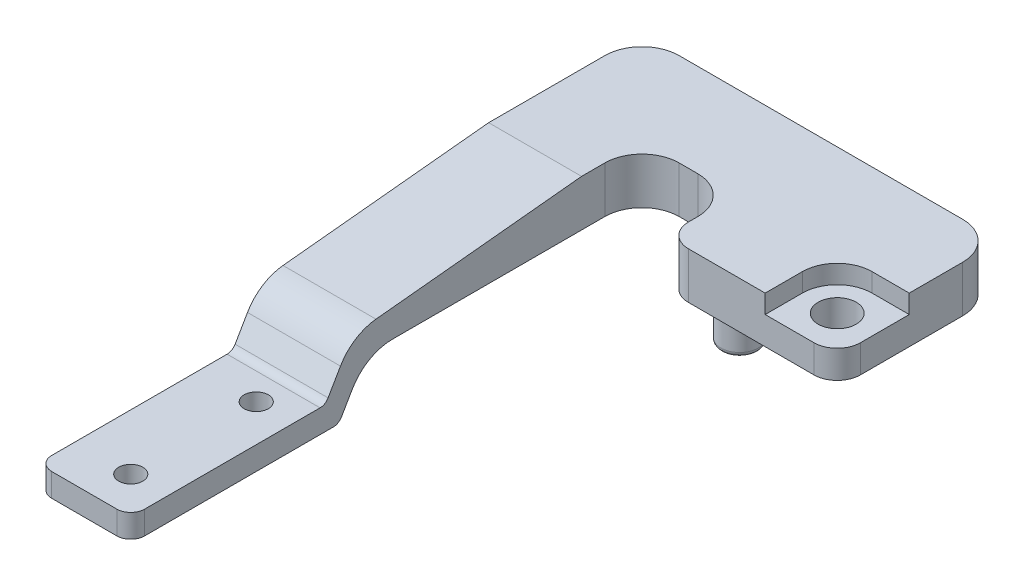
SolidWorks part; units mm, degrees
ref_plane "Front Plane" through (0, 0, 0) normal (0, 0, 1) x (1, 0, 0)
ref_plane "Top Plane" through (0, 0, 0) normal (0, 1, 0) x (1, 0, 0)
ref_plane "Right Plane" through (0, 0, 0) normal (1, 0, 0) x (0, 0, -1)
sketch "Sketch1" plane through (0, 0, 0) normal (0, 1, 0) x (1, 0, 0)
  line L12 (28.8534, -0.7933) -> (1.8534, -0.7933)
  line L13 (33.8534, 4.2067) -> (33.8534, 26.2067)
  line L14 (25.8534, 34.2067) -> (-3.1466, 34.2067)
  line L24 (-3.1466, 4.2067) -> (-3.1466, 6.2067)
  line L25 (-3.1466, 34.2067) -> (-35.1466, 34.2067)
  line L27 (-11.1466, 14.2067) -> (-15.1466, 14.2067)
  line L28 (-43.1466, 26.2067) -> (-43.1466, 4.2067)
  line L30 (-43.1466, 4.2067) -> (-43.1466, -92.7933)
  line L31 (-40.1466, -95.7933) -> (-26.1466, -95.7933)
  line L32 (-23.1466, 6.2067) -> (-23.1466, -92.7933)
  circle A0 centre (25.8534, 7.2067) radius 4.1
  circle A1 centre (4.8534, 7.2067) radius 4
  arc A25 (-15.1466, 14.2067) -> (-23.1466, 6.2067) centre (-15.1466, 6.2067) ccw
  arc A26 (-3.1466, 6.2067) -> (-11.1466, 14.2067) centre (-11.1466, 6.2067) ccw
  arc A27 (28.8534, -0.7933) -> (33.8534, 4.2067) centre (28.8534, 4.2067) ccw
  arc A28 (1.8534, -0.7933) -> (-3.1466, 4.2067) centre (1.8534, 4.2067) cw
  arc A29 (33.8534, 26.2067) -> (25.8534, 34.2067) centre (25.8534, 26.2067) ccw
  arc A30 (-35.1466, 34.2067) -> (-43.1466, 26.2067) centre (-35.1466, 26.2067) ccw
  arc A31 (-26.1466, -95.7933) -> (-23.1466, -92.7933) centre (-26.1466, -92.7933) ccw
  arc A32 (-43.1466, -92.7933) -> (-40.1466, -95.7933) centre (-40.1466, -92.7933) ccw
  circle A33 centre (-31.1466, -87.7933) radius 2.6
  circle A34 centre (-31.1466, -60.7933) radius 2.6
  dimension "D1" = 21
  dimension "D9" = 15
  dimension "D13" = 8
  dimension "D14" = 3
  dimension "D15" = 27
  dimension "D16" = 8
  dimension "D2" = 8
  dimension "D11" = 8
  dimension "D12" = 5
  dimension "D3" = 8
  dimension "D4" = 8
  dimension "D5" = 77
  dimension "D6" = 35
  dimension "D7" = 8
  dimension "D8" = 20
  dimension "D10" = 130
  dimension "D17" = 8
  dimension "D18" = 8
extrude "Boss-Extrude1" add sketch "Sketch1" along normal blind 10
sketch "Sketch2" plane through (0, 10, 0) normal (0, 1, 0) x (1, 0, 0)
  line L0 (25.8534, 14.7067) -> (33.8534, 14.7067)
  line L1 (33.8534, 4.2067) -> (33.8534, 26.2067) construction
  line L2 (33.8534, 14.7067) -> (33.8534, 4.2067)
  line L3 (18.3534, 7.2067) -> (18.3534, -0.7933)
  line L4 (1.8534, -0.7933) -> (28.8534, -0.7933) construction
  line L5 (18.3534, -0.7933) -> (28.8534, -0.7933)
  arc A0 (25.8534, 14.7067) -> (18.3534, 7.2067) centre (25.8534, 7.2067) ccw
  arc A1 (28.8534, -0.7933) -> (33.8534, 4.2067) centre (28.8534, 4.2067) ccw
extrude "Cut-Extrude1" cut sketch "Sketch2" against normal blind 4
sketch "Sketch5" plane through (0, 0, 0) normal (0, -1, 0) x (-1, 0, 0)
  circle A0 centre (-4.8534, 7.2067) radius 4
extrude "Boss-Extrude2" add sketch "Sketch5" along normal blind 10 and the other way up to surface (10 mm away) other way up to face at (-6.1793, 10, 9.4654)
fillet "Fillet1" radius 1 2 edges at (4.8534, -10, -11.2067) (4.8534, 0, -3.2067)
sketch "Sketch6" plane through (0, 0, 0) normal (0, -1, 0) x (1, 0, 0)
  line L0 (-26.1466, 95.7933) -> (-40.1466, 95.7933)
  line L1 (-43.1466, 92.7933) -> (-43.1466, 51.0315)
  line L2 (-43.1466, -26.2067) -> (-43.1466, 92.7933) construction
  line L3 (-43.1466, 51.0315) -> (-23.1466, 51.0315)
  line L4 (-23.1466, 92.7933) -> (-23.1466, -6.2067) construction
  line L5 (-23.1466, 51.0315) -> (-23.1466, 92.7933)
  arc A0 (-40.1466, 95.7933) -> (-43.1466, 92.7933) centre (-40.1466, 92.7933) ccw
  arc A1 (-23.1466, 92.7933) -> (-26.1466, 95.7933) centre (-26.1466, 92.7933) ccw
  circle A2 centre (-31.1466, 87.7933) radius 2.6
  circle A3 centre (-31.1466, 60.7933) radius 2.6
extrude "Boss-Extrude3" add sketch "Sketch6" along normal blind 10
sketch "Sketch7" plane through (-23.1466, 0, 0) normal (1, 0, 0) x (0, 0, -1)
  line L0 (-51.0315, -10) -> (-45.2327, 0)
  line L1 (-51.0315, 0) -> (6.2067, 0) construction
  line L2 (-45.2327, 0) -> (-51.0315, 0)
  line L3 (-51.0315, 0) -> (-51.0315, -10)
extrude "Boss-Extrude4" add sketch "Sketch7" against normal up to surface (20 mm away) up to face at (-43.1466, 0, 39.206)
sketch "Sketch8" plane through (-43.1466, 0, 0) normal (-1, 0, 0) x (0, 0, 1)
  line L0 (53.9119, -5) -> (48.1132, 5)
  line L1 (48.1132, 5) -> (-1.2067, 10)
  line L2 (-26.2067, 10) -> (92.7933, 10) construction
  line L3 (-1.2067, 10) -> (103.6773, 10)
  line L4 (103.6773, 10) -> (103.6773, -5)
  line L5 (103.6773, -5) -> (53.9119, -5)
  line L6 (92.7933, -10) -> (51.0315, -10) construction
  line L7 (45.2327, 0) -> (51.0315, -10) construction
  line L9 (-26.2067, 0) -> (45.2327, 0) construction
  line L10 (-26.2067, 10) -> (-26.2067, 0) construction
  dimension "D1" = 5
  dimension "D2" = 5
  dimension "D3" = 5
  dimension "D4" = 25
extrude "Cut-Extrude2" cut sketch "Sketch8" against normal up to surface (20 mm away) up to face at (-23.1466, 0, 44.9062)
fillet "Fillet2" radius 10 2 edges at (-33.1466, 5, 48.1132) (-33.1466, 0, 45.2327)
fillet "Fillet3" radius 2 2 edges at (-33.1466, -10, 51.0315) (-33.1466, -5, 53.9119)
